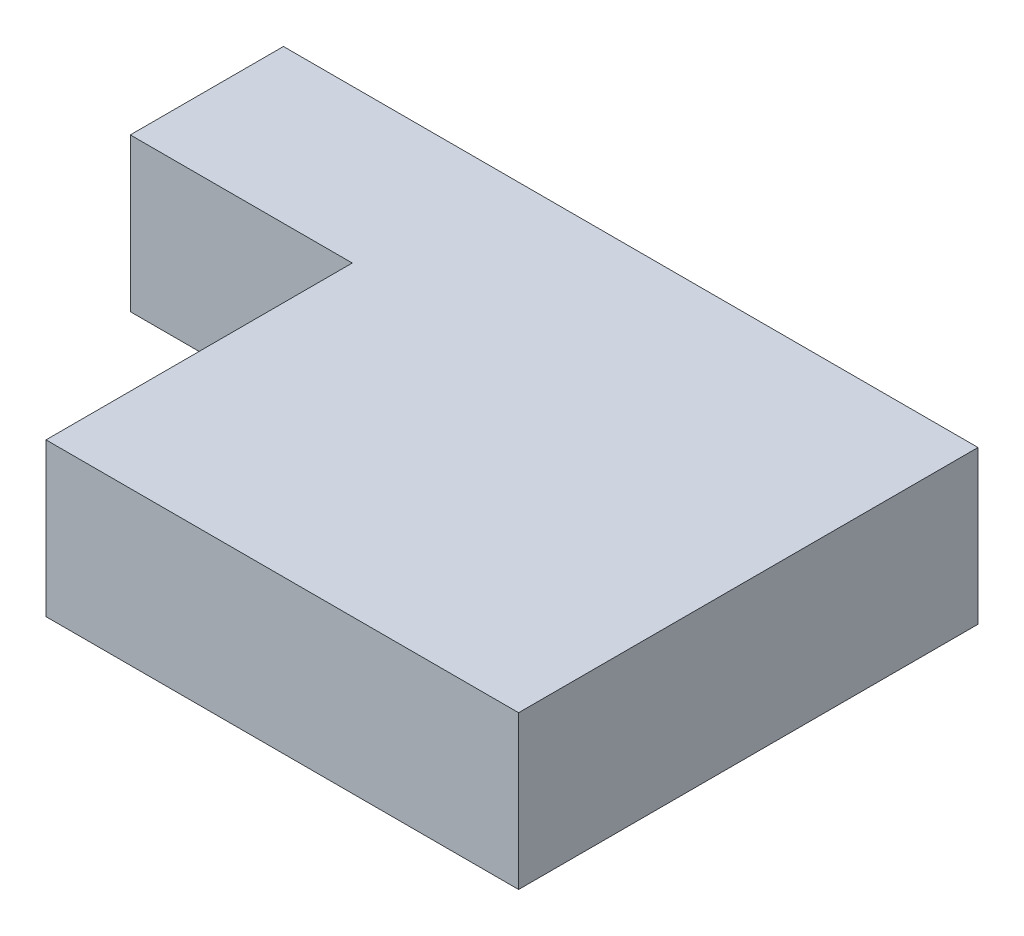
SolidWorks part; units mm, degrees
ref_plane "Front Plane" through (0, 0, 0) normal (0, 0, 1) x (1, 0, 0)
ref_plane "Top Plane" through (0, 0, 0) normal (0, 1, 0) x (1, 0, 0)
ref_plane "Right Plane" through (0, 0, 0) normal (1, 0, 0) x (0, 0, -1)
sketch "Sketch1" plane through (0, 0, 0) normal (0, 1, 0) x (1, 0, 0)
  line L1 (0, 0) -> (21.7714, 0)
  line L2 (0, 0) -> (0, 14.4)
  line L3 (0, 14.4) -> (21.7714, 14.4)
  line L4 (21.7714, 0) -> (21.7714, 14.4)
  line L5 (0, 0) -> (21.7714, 14.4) construction
  line L6 (0, 14.4) -> (21.7714, 0) construction
  point P4 (10.8857, 7.2)
  dimension "D1" = 14.4
  dimension "D2" = 21.7714
extrude "Boss-Extrude1" add sketch "Sketch1" along normal blind 4.8
sketch "Sketch2" plane through (0, 4.8, 0) normal (0, 1, 0) x (1, 0, 0)
  line L1 (0, 0) -> (6.9571, 0)
  line L2 (0, 0) -> (0, 9.6)
  line L3 (0, 9.6) -> (6.9571, 9.6)
  line L4 (6.9571, 0) -> (6.9571, 9.6)
  line L5 (0, 0) -> (6.9571, 9.6) construction
  line L6 (0, 9.6) -> (6.9571, 0) construction
  point P4 (3.4786, 4.8)
  dimension "D1" = 6.9571
  dimension "D2" = 9.6
extrude "Cut-Extrude1" cut sketch "Sketch2" against normal through all
equation "\"MDF\"= 4.8mm"
equation "\"Foamcore\"= 4.6mm"
equation "\"GMaterial\"= \"MDF\""
equation "\"PCB\" = 1.6mm"
equation "\"BaseWidth\" = 10in"
equation "\"SkidLength\" = 1in"
equation "\"SkidClearance\" = 0.4in"
equation "\"MotorMountLength\" = 2in"
equation "\"MotorMountWidth\" = \"GMaterial\""
equation "\"MotorMountHeight\" = 2.25in"
equation "\"UnoStackWidth\" = 77.4mm"
equation "\"UnoStackLength\" = 79.8mm"
equation "\"UnoStackHeight\" = 34.2mm"
equation "\"TallHexRiserHeight\" = 22.2mm"
equation "\"PingPongBallSize\" = 40mm"
equation "\"BarrelLength\" = 9in"
equation "\"BarrelSize\" = \"PingPongBallSize\""
equation "\"PlatformLength\" = 4in"
equation "\"PlatformWidth\" = 6in"
equation "\"WheelDiameter\"=2.99213"
equation "\"ServoMountHeight\"=2.49223"
equation "\"ServoGearHeight\" = 0.95330261in"
equation "\"ServoMountLength\"= 1.53774"
equation "\"PivotHoleRadius\"= 0.616358"
equation "\"PlatformMountHeight\" = 3.19"
equation "\"TensionOffSet\"= .3mm"
equation "\"MotorMountWedge\"=0.333333"
equation "\"LaserCutterOffset\"= .3mm"
equation "\"BumperWidth\"=11"
equation "\"PitcherWheelCompression\" = 2.5mm"
equation "\"PitchingWheelWidth\" = 26.2mm"
equation "\"PitchingWheelDiameter\" = 65.5mm"
equation "\"PitchingWheelMountOffset\" = 8.4mm"
equation "\"PitchingWheelInnerDiameter\" = 45.5mm"
equation "\"PitchingWheelBoltShoulder\" = 4.5mm"
equation "\"BrassCouplingLength\" = 18mm"
equation "\"PitchingMotorHeight\" = 57.0mm"
equation "\"PitchingMotorShaftTopHeight\" = \"PitchingMotorHeight\" - 44.1mm"
equation "\"PitchingMotorBodyHeight\" = 38mm"
equation "\"PitchingMotorTopShoulderHeight\" = 40.6mm - \"PitchingMotorBodyHeight\" "
equation "\"PitchingMotorBottomShoulderHeight\" = 40.2mm - \"PitchingMotorBodyHeight\""
equation "\"PitchingMotorBottomShaftHeight\" = \"PitchingMotorHeight\" - \"PitchingMotorShaftTopHeight\" - \"PitchingMotorTopShoulderHeight\" - \"PitchingMotorBodyHeight\" - \"PitchingMotorBottomShoulderHeight\""
equation "\"PitchingMotorShaftDiameter\" = 2.2mm"
equation "\"PitchingMotorBodyDiameter\" = 27.4mm"
equation "\"PitchingMotorTopShoulderDiameter\" = 9.8mm"
equation "\"PitchingMotorBottomShoulderDiameter\" = 9.8mm"
equation "\"BrassCouplingHexSize\" = 12mm"
equation "\"BrassCouplingBoreSize\" = 3.17mm"
equation "\"PitchingMotorMountingHoleDistance\" = 16mm"
equation "\"Acrylic\" = 4.4mm"
equation "\"PitchingMotorDistance\" = \"PitchingWheelDiameter\" + \"PingPongBallSize\" - \"PitcherWheelCompression\"*2"
equation "\"PitchingMotorPlatformOffset\"=1"
equation "\"ServoPlatformOffset\"=1.64173"
equation "\"BallBearingDiameter\" = 22mm"
equation "\"BallBearingWidth\" = 9mm"
equation "\"BallBearingHexShoulder\" = 9mm - 5.9mm"
equation "\"BallBearingHexSize\" = .36in"
equation "\"PlatformMountFootLength\"=0.857143"
equation "\"WheelWidth\"= 26mm"
equation "\"ServoMountReductionBackHeight\"=2.25"
equation "\"PlatformBottomWidthThird\" =  0.857143in"
equation "\"PlatformMountBackReductionHeight\"= 2.5in"
equation "\"PlatformMountBackReductionWidth\"= 3/7in"
equation "\"PlatformMountFrontReductionWidth\" =  1.46226in"
equation "\"PlatformMountFrontReductionHeight\" = 2.5in"
equation "\"D1@Sketch1\"=\"GMaterial\"*3"
equation "\"D2@Sketch1\"=\"PlatformMountFootLength\""
equation "\"D1@Boss-Extrude1\"=\"GMaterial\""
equation "\"D2@Sketch2\"=\"GMaterial\"*2"
equation "\"D1@Sketch2\"=\"PlatformMountFootLength\"/3 - \"LaserCutterOffset\""
